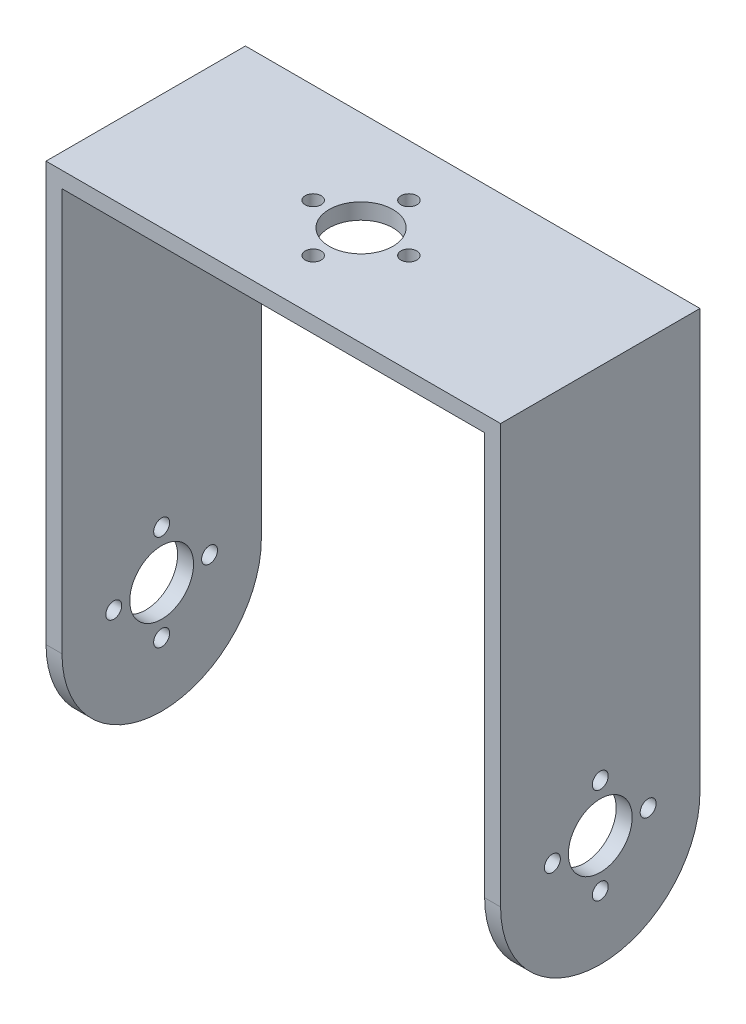
SolidWorks part; units mm, degrees
material "1060 Alloy"
ref_plane "Front Plane" through (0, 0, 0) normal (0, 0, 1) x (1, 0, 0)
ref_plane "Top Plane" through (0, 0, 0) normal (0, 1, 0) x (1, 0, 0)
ref_plane "Right Plane" through (0, 0, 0) normal (1, 0, 0) x (0, 0, -1)
sketch "Sketch3" plane through (0, 0, 0) normal (0, 0, 1) x (1, 0, 0)
  line L0 (-79.9255, 45.3865) -> (-27.043, 45.3865)
  line L1 (-81.9255, 45.3865) -> (-79.9255, 45.3865)
  line L2 (-81.9255, 45.3865) -> (-81.9255, -19.6135)
  line L3 (-81.9255, -19.6135) -> (-79.9255, -19.6135)
  line L4 (-79.9255, 43.39) -> (-79.9255, -19.6135)
  line L5 (-81.9255, 45.3865) -> (-79.9255, -19.6135) construction
  line L6 (-81.9255, -19.6135) -> (-79.9255, 45.3865) construction
  line L7 (-79.9255, 43.39) -> (-26.9255, 43.39)
  line L8 (-26.9255, 43.39) -> (-26.9255, -19.6135)
  line L9 (-27.043, 45.3865) -> (-24.9255, 45.3865)
  line L10 (-26.9255, -19.6135) -> (-24.9255, -19.6135)
  line L11 (-24.9255, 45.3865) -> (-24.9255, -19.6135)
  point P0 (-80.9255, 12.8865)
  dimension "D1" = 65
  dimension "D2" = 2
  dimension "D3" = 2
  dimension "D4" = 57
  dimension "D5" = 2
extrude "Boss-Extrude2" add sketch "Sketch3" along normal blind 25
sketch "Sketch4" plane through (0, 45.3865, 0) normal (0, 1, 0) x (1, 0, 0)
  line L0 (-81.9255, -25) -> (-81.9255, 0) construction
  line L3 (-24.9255, -25) -> (-81.9255, -25) construction
  circle A0 centre (-54.9255, -12.5) radius 4
  dimension "D1" = 27
  dimension "D2" = 12.5
extrude "Cut-Extrude1" cut sketch "Sketch4" against normal through all
sketch "Sketch6" plane through (-81.9255, 0, 0) normal (-1, 0, 0) x (0, 0, 1)
  line L1 (25, 45.3865) -> (0, 45.3865) construction
  line L2 (0, 45.3865) -> (0, -19.6135) construction
  circle A0 centre (12.5, -5.6135) radius 4
  dimension "D1" = 51
  dimension "D2" = 12.5
extrude "Cut-Extrude2" cut sketch "Sketch6" against normal through all
sketch "Sketch8" plane through (-81.9255, 0, 0) normal (-1, 0, 0) x (0, 0, 1)
  line L0 (25, 45.3865) -> (25, -19.6135) construction
  line L1 (25, -19.6135) -> (0, -19.6135) construction
  line L2 (0, 45.3865) -> (0, -19.6135) construction
  line L3 (25, -19.6135) -> (0, -19.6135)
  line L4 (0, 45.3865) -> (0, -19.6135)
  line L5 (25, 45.3865) -> (25, -19.6135)
  circle A0 centre (12.5, -7.1135) radius 12.5
  line M4 (0, -19.6135) -> (25, -19.6135)
  line M5 (25, -19.6135) -> (25, 45.3865)
extrude "Cut-Extrude3" cut sketch "Sketch8" against normal through all contours A0 L4 M4 | A0 L3 M5
sketch "Sketch9" plane through (-24.9255, 0, 0) normal (1, 0, 0) x (0, 0, -1)
  circle A0 centre (-12.5, -11.6186) radius 1
  circle A2 centre (-18.5051, -5.6135) radius 1
  circle A3 centre (-6.4949, -5.6135) radius 1
  circle A4 centre (-12.5, 0.3916) radius 1
  circle A5 centre (-12.5, -5.6135) radius 6.0051 construction
  point P13 (-12.5, -5.6135)
  point P15 (-12.5, -5.6135)
  dimension "D1" = 4
  dimension "D3" = 2
  dimension "D2" = 6.0051
extrude "Cut-Extrude4" cut sketch "Sketch9" against normal through all
sketch "Sketch10" plane through (0, 45.3865, 0) normal (0, 1, 0) x (1, 0, 0)
  circle A0 centre (-48.9255, -12.5) radius 1
  circle A1 centre (-54.9255, -12.5) radius 6 construction
  circle A2 centre (-54.9255, -6.5) radius 1
  circle A3 centre (-54.9255, -18.5) radius 1
  circle A4 centre (-60.9255, -12.5) radius 1
  point P13 (-54.9255, -12.5)
  point P16 (-54.9255, -12.5)
  dimension "D1" = 4
  dimension "D3" = 12
  dimension "D5" = 2
extrude "Cut-Extrude5" cut sketch "Sketch10" against normal through all
